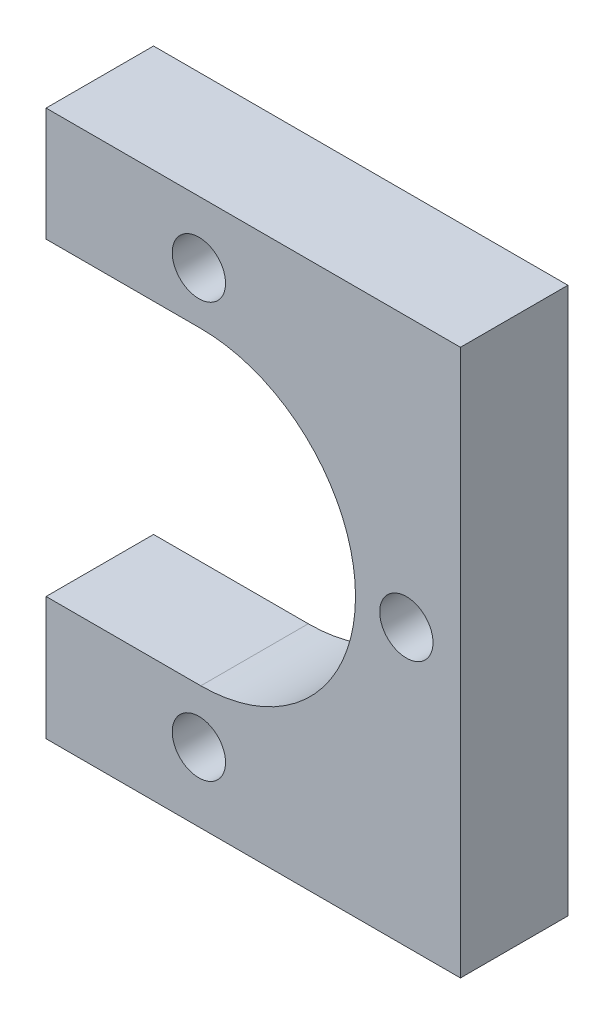
SolidWorks part; units mm, degrees
ref_plane "Plano frontal" through (0, 0, 0) normal (0, 0, 1) x (1, 0, 0)
ref_plane "Plano superior" through (0, 0, 0) normal (0, 1, 0) x (1, 0, 0)
ref_plane "Plano direito" through (0, 0, 0) normal (1, 0, 0) x (0, 0, -1)
sketch "Esboço1" plane through (0, 0, 0) normal (0, 0, 1) x (1, 0, 0)
  line L0 (26.91, 28.735) -> (-26.91, -28.735) construction
  line L1 (-26.91, 28.735) -> (26.91, 28.735)
  line L2 (-26.91, 28.735) -> (-26.91, -28.735)
  line L3 (-26.91, -28.735) -> (26.91, -28.735)
  line L4 (26.91, 28.735) -> (26.91, -28.735)
  dimension "D1" = 57.47
  dimension "D2" = 53.82
extrude "Ressalto-extrusão1" add sketch "Esboço1" along normal blind 11.11
sketch "Esboço2" plane through (0, 0, 11.11) normal (0, 0, 1) x (1, 0, 0)
  line L0 (-15.9291, 15.995) -> (-15.9291, 28.735) construction
  line L1 (26.91, 28.735) -> (-26.91, 28.735) construction
  line L2 (-15.9291, -15.995) -> (-15.9291, -28.735)
  line L3 (-26.91, -28.735) -> (26.91, -28.735) construction
  line L4 (0.0659, 15.995) -> (-15.9291, 15.995)
  line L5 (0.0659, -15.995) -> (-15.9291, -15.995)
  line L6 (0, 28.735) -> (-15.9291, 28.735)
  line L7 (-15.9291, 28.735) -> (-15.9291, 15.995)
  line L8 (0, -28.735) -> (-15.9291, -28.735)
  line L9 (-15.9291, -28.735) -> (-16.0516, -26.7828)
  line L10 (0, -28.735) -> (26.91, -28.735)
  line L11 (26.91, -28.735) -> (26.91, 28.735)
  line L12 (26.91, 28.735) -> (0, 28.735)
  arc A0 (0.0659, -15.995) -> (0.0659, 15.995) centre (0.0659, 0) ccw
  line M2 (-26.91, -28.735) -> (26.91, -28.735)
  line M3 (26.91, -28.735) -> (26.91, 28.735)
  line M4 (26.91, 28.735) -> (-26.91, 28.735)
  dimension "D1" = 15.995
extrude "Ressalto-extrusão2" add sketch "Esboço2" along normal blind 11.11 contours A0 L5 L2 L7 L4 M2 M3 M4
sketch "Esboço3" plane through (0, 0, 0) normal (0, 0, -1) x (-1, 0, 0)
  line L4 (26.91, -28.735) -> (26.91, 28.735)
  line L5 (26.91, 28.735) -> (-26.91, 28.735)
  line L6 (-26.91, 28.735) -> (-26.91, -28.735)
  line L7 (-26.91, -28.735) -> (26.91, -28.735)
  line L8 (26.91, -28.735) -> (26.91, 28.735)
  line L9 (26.91, 28.735) -> (-26.91, 28.735)
  line L10 (-26.91, 28.735) -> (-26.91, -28.735)
  line L11 (-26.91, -28.735) -> (26.91, -28.735)
  dimension "D1" = 0
sketch "Esboço4" plane through (0, 0, 22.22) normal (0, 0, 1) x (1, 0, 0)
  line L0 (-0.1319, 26.8441) -> (-0.1319, -26.9759) construction
  line L1 (26.7781, -0.0659) -> (-27.0419, -0.0659) construction
  circle A0 centre (21.3181, -0.1319) radius 2.755
  circle A1 centre (-0.1319, -21.5819) radius 2.755
  circle A3 centre (-0.1319, 21.3181) radius 2.755
extrude "Corte-extrusão2" cut sketch "Esboço4" against normal blind 11.11
extrude "Corte-extrusão3" cut sketch "Esboço3" against normal blind 11.11
sketch "Esboço5" plane through (0, 0, 11.11) normal (0, 0, -1) x (-1, 0, 0)
  line L0 (15.9291, 28.735) -> (15.9291, 15.995) construction
  line L1 (-26.91, 28.735) -> (15.9291, 28.735)
  line L2 (-26.91, 28.735) -> (-26.91, 27.735)
  line L3 (-26.91, 27.735) -> (15.9291, 27.735)
  line L4 (15.9291, 28.735) -> (15.9291, 27.735)
  dimension "D1" = 1
extrude "Corte-extrusão4" cut sketch "Esboço5" against normal up to surface (11.11 mm away) up to face at (2.6231, 21.3181, 22.22)
